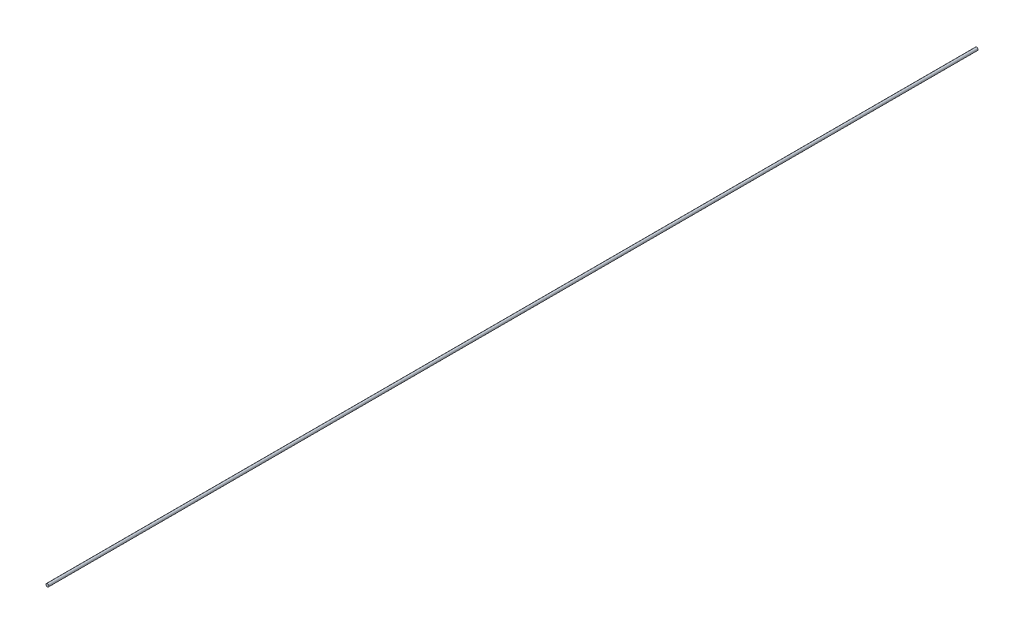
SolidWorks part; units mm, degrees
ref_plane "Front Plane" through (0, 0, 0) normal (0, 0, 1) x (1, 0, 0)
ref_plane "Top Plane" through (0, 0, 0) normal (0, 1, 0) x (1, 0, 0)
ref_plane "Right Plane" through (0, 0, 0) normal (1, 0, 0) x (0, 0, -1)
sketch "Sketch1" plane through (0, 0, 0) normal (0, 0, 1) x (1, 0, 0)
  circle A0 centre (0, 0) radius 0.1
  dimension "D1" = 0.2
extrude "Boss-Extrude1" add sketch "Sketch1" along normal blind 65
